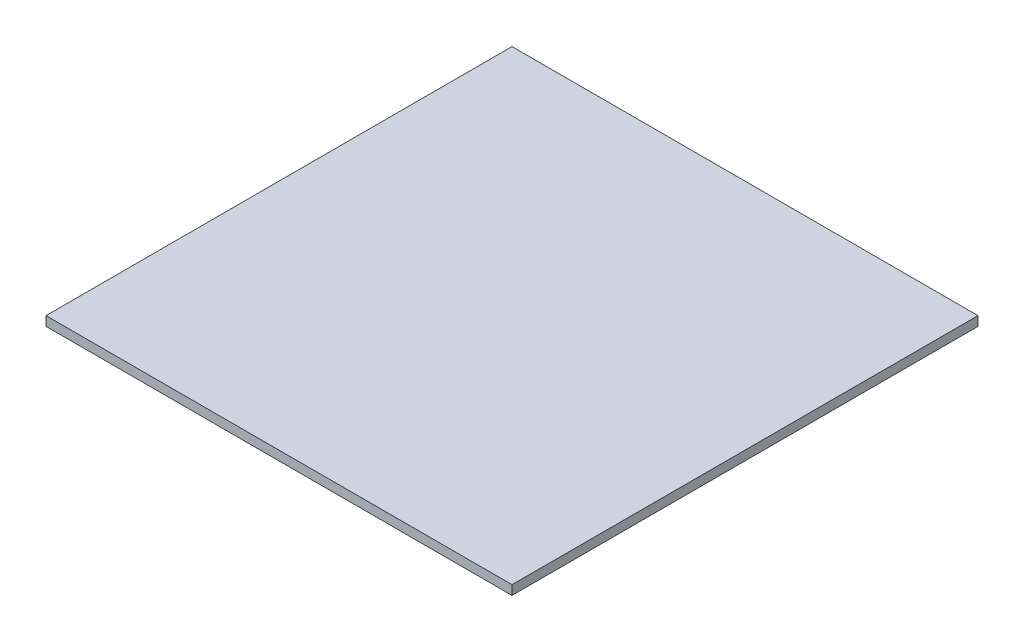
SolidWorks part; units mm, degrees
ref_plane "Płaszczyzna przednia" through (0, 0, 0) normal (0, 0, 1) x (1, 0, 0)
ref_plane "Płaszczyzna górna" through (0, 0, 0) normal (0, 1, 0) x (1, 0, 0)
ref_plane "Płaszczyzna prawa" through (0, 0, 0) normal (1, 0, 0) x (0, 0, -1)
sketch "Szkic1" plane through (0, 0, 0) normal (0, 1, 0) x (1, 0, 0)
  line L1 (0, 0) -> (500, 0)
  line L2 (0, 0) -> (0, 500)
  line L3 (0, 500) -> (500, 500)
  line L4 (500, 0) -> (500, 500)
  dimension "D1" = 500
extrude "Dodanie-wyciągnięcie1" add sketch "Szkic1" along normal blind 10
